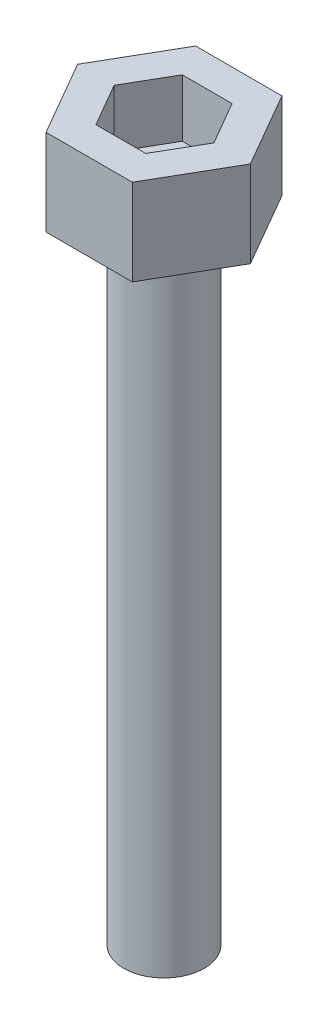
SolidWorks part; units mm, degrees
ref_plane "Front Plane" through (0, 0, 0) normal (0, 0, 1) x (1, 0, 0)
ref_plane "Top Plane" through (0, 0, 0) normal (0, 1, 0) x (1, 0, 0)
ref_plane "Right Plane" through (0, 0, 0) normal (1, 0, 0) x (0, 0, -1)
sketch "Sketch1" plane through (0, 0, 0) normal (0, 1, 0) x (1, 0, 0)
  circle A0 centre (0, 0) radius 1.4
  dimension "D1" = 2.8
extrude "Boss-Extrude1" add sketch "Sketch1" along normal blind 22
sketch "Sketch2" plane through (0, 22, 0) normal (0, 1, 0) x (1, 0, 0)
  line L1 (3, 0) -> (1.5, 2.5981)
  line L2 (1.5, 2.5981) -> (-1.5, 2.5981)
  line L3 (-1.5, 2.5981) -> (-3, 0)
  line L4 (-3, 0) -> (-1.5, -2.5981)
  line L5 (-1.5, -2.5981) -> (1.5, -2.5981)
  line L6 (1.5, -2.5981) -> (3, 0)
  circle A1 centre (0, 0) radius 2.5981 construction
extrude "Boss-Extrude2" add sketch "Sketch2" along normal blind 3
sketch "Sketch3" plane through (0, 25, 0) normal (0, 1, 0) x (1, 0, 0)
  line L1 (1.7321, 0) -> (0.866, 1.5)
  line L2 (0.866, 1.5) -> (-0.866, 1.5)
  line L3 (-0.866, 1.5) -> (-1.7321, 0)
  line L4 (-1.7321, 0) -> (-0.866, -1.5)
  line L5 (-0.866, -1.5) -> (0.866, -1.5)
  line L6 (0.866, -1.5) -> (1.7321, 0)
  circle A0 centre (0, 0) radius 1.5 construction
  dimension "D1" = 3
extrude "Cut-Extrude1" cut sketch "Sketch3" against normal blind 2
